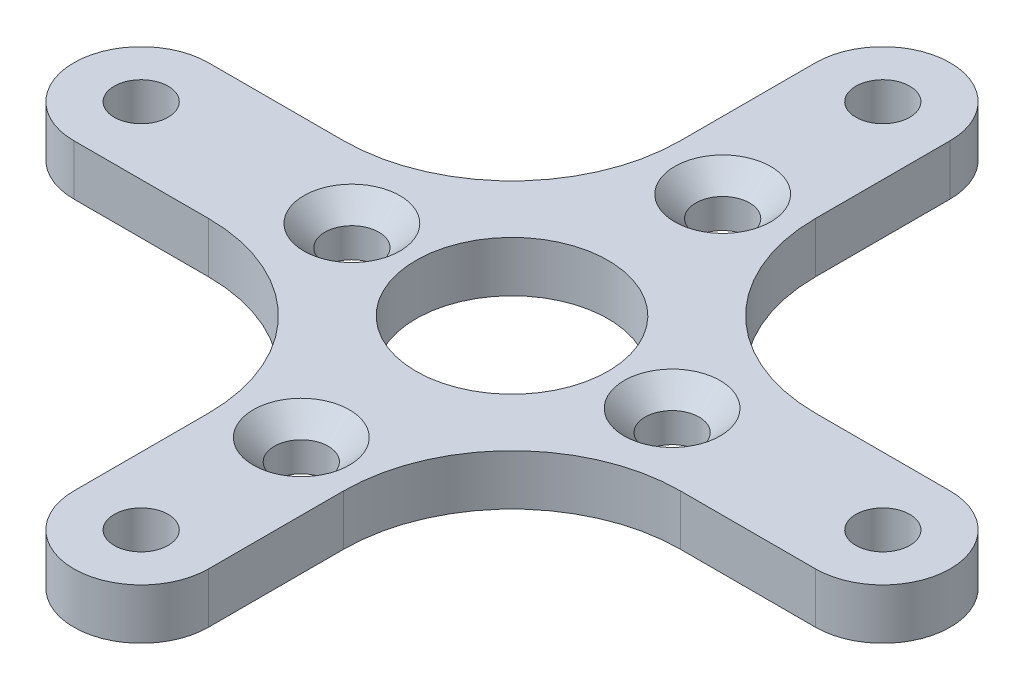
SolidWorks part; units mm, degrees
material "1023 Carbon Steel Sheet (SS)"
ref_plane "Front Plane" through (0, 0, 0) normal (0, 0, 1) x (1, 0, 0)
ref_plane "Top Plane" through (0, 0, 0) normal (0, 1, 0) x (1, 0, 0)
ref_plane "Right Plane" through (0, 0, 0) normal (1, 0, 0) x (0, 0, -1)
sketch "Sketch1" plane through (0, 0, 0) normal (0, 1, 0) x (1, 0, 0)
  line L0 (-4, 22) -> (-4, 4)
  line L1 (-4, 4) -> (-22, 4)
  line L2 (-22, 4) -> (-22, -4)
  line L3 (-22, -4) -> (-4, -4)
  line L4 (-4, -4) -> (-4, -22)
  line L5 (-4, -22) -> (4, -22)
  line L6 (4, -22) -> (4, -4)
  line L7 (4, -4) -> (22, -4)
  line L8 (22, -4) -> (22, 4)
  line L9 (22, 4) -> (4, 4)
  line L10 (4, 4) -> (4, 22)
  line L11 (4, 22) -> (-4, 22)
  arc A0 (-22, 4) -> (-22, -4) centre (-22, 0) ccw
  arc A1 (-4, 22) -> (4, 22) centre (0, 22) cw
  arc A2 (22, 4) -> (22, -4) centre (22, 0) cw
  arc A3 (4, -22) -> (-4, -22) centre (0, -22) cw
  point P2 (-22, 0)
  point P14 (0, -22)
  point P18 (0, 26)
  point P21 (0, -26)
  dimension "D2" = 52
  dimension "D1" = 44
extrude "Boss-Extrude1" add sketch "Sketch1" along normal blind 3 contours L10 L11 L0 L1 L2 L3 L4 L5 L6 L7 L8 L9 | A1 L11 | A2 L8 | L2 A0 | A3 L5
sketch "Sketch2" plane through (0, 3, 0) normal (0, 1, 0) x (1, 0, 0)
  line L0 (-9.5, 0) -> (9.5, 0)
  line L1 (0, 12.5) -> (0, -12.5)
  circle A0 centre (0, 12.5) radius 1.6
  circle A1 centre (9.5, 0) radius 1.6
  circle A2 centre (0, -12.5) radius 1.6
  circle A3 centre (-9.5, 0) radius 1.6
  circle A4 centre (-22, 0) radius 1.6
  circle A5 centre (22, 0) radius 1.6
  circle A6 centre (0, 22) radius 1.6
  circle A7 centre (0, -22) radius 1.6
  circle A8 centre (0, 0) radius 22 construction
  point P16 (0, 0)
  point P20 (0, 0)
  dimension "D2" = 44
  dimension "D4" = 3.2
  dimension "D1" = 19
  dimension "D3" = 25
extrude "Cut-Extrude1" cut sketch "Sketch2" against normal blind 25 contours A4 | A6 | A7 | A5 | A0 | A3 | A2 | A1
chamfer "Chamfer1" distance 1.25 angle 45 4 edges at (0, 3, 14.1) (9.5, 3, 1.6) (0, 3, -10.9) (-9.5, 3, 1.6)
fillet "Fillet1" radius 10 4 edges at (-4, 1.5, -4) (4, 1.5, -4) (4, 1.5, 4) (-4, 1.5, 4)
sketch "Sketch3" plane through (0, 3, 0) normal (0, 1, 0) x (1, 0, 0)
  circle A0 centre (0, 0) radius 5.7
  dimension "D1" = 11.4
extrude "Cut-Extrude2" cut sketch "Sketch3" against normal blind 3
